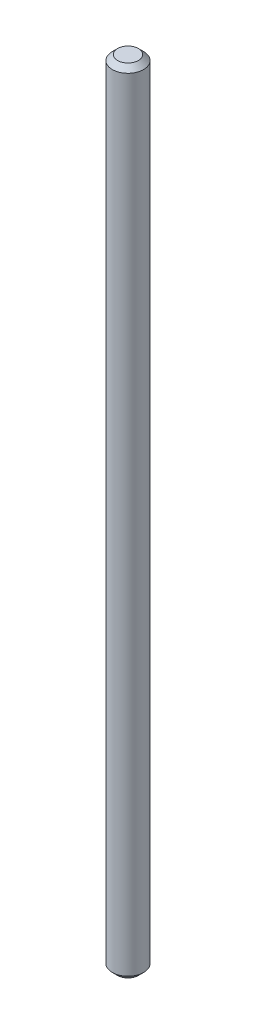
SolidWorks part; units mm, degrees
material "AISI 1035 Steel (SS)"
ref_plane "Front Plane" through (0, 0, 0) normal (0, 0, 1) x (1, 0, 0)
ref_plane "Top Plane" through (0, 0, 0) normal (0, 1, 0) x (1, 0, 0)
ref_plane "Right Plane" through (0, 0, 0) normal (1, 0, 0) x (0, 0, -1)
sketch "Sketch2" plane through (0, 0, 0) normal (0, 1, 0) x (1, 0, 0)
  circle A0 centre (0, 0) radius 1.5
  dimension "D1" = 3
extrude "Boss-Extrude1" add sketch "Sketch2" along normal blind 76
chamfer "Chamfer1" distance 0.5 angle 45 2 edges at (0, 76, 1.5) (0, 0, 1.5)
